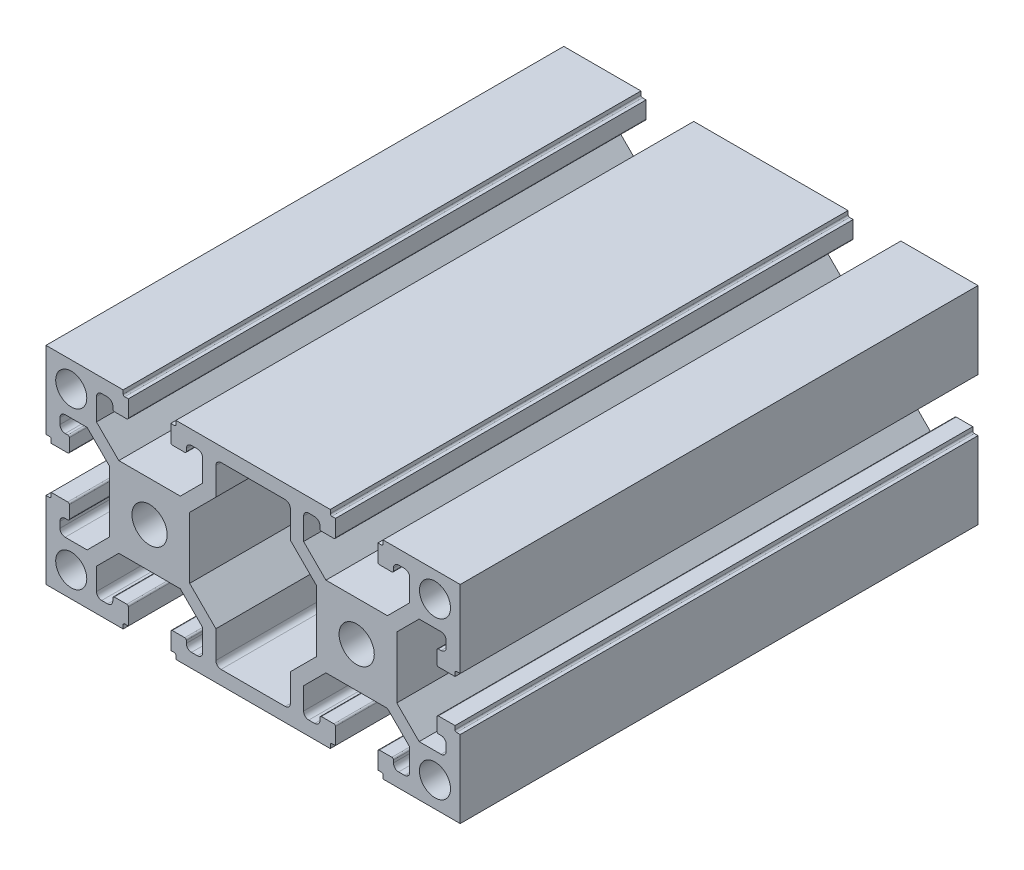
SolidWorks part; units mm, degrees
ref_plane "前视基准面" through (0, 0, 0) normal (0, 0, 1) x (1, 0, 0)
ref_plane "上视基准面" through (0, 0, 0) normal (0, 1, 0) x (1, 0, 0)
ref_plane "右视基准面" through (0, 0, 0) normal (1, 0, 0) x (0, 0, -1)
sketch "草图1" plane through (0, 0, 0) normal (0, 0, 1) x (1, 0, 0)
  line L0 (-26.1884, 19.243) -> (-41.0884, 19.243)
  line L1 (-41.0884, 19.243) -> (-41.0884, 4.343)
  line L2 (-33.1486, 9.493) -> (-37.3884, 9.493)
  line L3 (-38.3884, 8.493) -> (-38.3884, 7.343)
  line L4 (-37.3884, 6.343) -> (-36.8884, 6.343)
  line L5 (-36.5884, 6.043) -> (-36.5884, 3.643)
  line L6 (-36.8884, 3.343) -> (-40.0884, 3.343)
  line L8 (-41.0884, 4.343) -> (-40.3884, 4.343)
  line L9 (-40.0884, 4.043) -> (-40.0884, 3.343)
  line L10 (-28.8384, 5.1828) -> (-28.8384, -6.6968)
  line L11 (-27.0282, -8.507) -> (-15.1486, -8.507)
  line L12 (-15.1486, 6.993) -> (-27.0282, 6.993)
  line L13 (-26.1884, 19.243) -> (-26.1884, 18.543)
  line L14 (-25.8884, 18.243) -> (-25.1884, 18.243)
  line L15 (-31.3384, 11.3032) -> (-31.3384, 15.543)
  line L16 (-30.3384, 16.543) -> (-29.1884, 16.543)
  line L17 (-28.1884, 15.543) -> (-28.1884, 15.043)
  line L18 (-27.8884, 14.743) -> (-25.4884, 14.743)
  line L19 (-25.1884, 15.043) -> (-25.1884, 18.243)
  line L20 (-15.9884, 19.243) -> (-1.0884, 19.243)
  line L22 (-10.8384, 11.3032) -> (-10.8384, 15.543)
  line L23 (-8.2784, 10.2428) -> (-8.2784, 15.543)
  line L24 (-11.8384, 16.543) -> (-12.9884, 16.543)
  line L25 (-13.9884, 15.543) -> (-13.9884, 15.043)
  line L26 (-14.2884, 14.743) -> (-16.6884, 14.743)
  line L27 (-16.9884, 15.043) -> (-16.9884, 18.243)
  line L28 (-15.9884, 19.243) -> (-15.9884, 18.543)
  line L29 (-16.2884, 18.243) -> (-16.9884, 18.243)
  line L30 (-26.1884, -20.757) -> (-41.0884, -20.757)
  line L31 (-41.0884, -20.757) -> (-41.0884, -5.857)
  line L33 (-33.1486, -11.007) -> (-37.3884, -11.007)
  line L34 (-38.3884, -10.007) -> (-38.3884, -8.857)
  line L35 (-37.3884, -7.857) -> (-36.8884, -7.857)
  line L36 (-36.5884, -7.557) -> (-36.5884, -5.157)
  line L37 (-36.8884, -4.857) -> (-40.0884, -4.857)
  line L38 (-41.0884, -5.857) -> (-40.3884, -5.857)
  line L39 (-40.0884, -5.557) -> (-40.0884, -4.857)
  line L40 (-31.3384, -12.8172) -> (-31.3384, -17.057)
  line L41 (-30.3384, -18.057) -> (-29.1884, -18.057)
  line L42 (-28.1884, -17.057) -> (-28.1884, -16.557)
  line L43 (-27.8884, -16.257) -> (-25.4884, -16.257)
  line L44 (-25.1884, -16.557) -> (-25.1884, -19.757)
  line L45 (-26.1884, -20.757) -> (-26.1884, -20.057)
  line L46 (-25.8884, -19.757) -> (-25.1884, -19.757)
  line L47 (-15.9884, -20.757) -> (-1.0884, -20.757)
  line L49 (-10.8384, -12.8172) -> (-10.8384, -17.057)
  line L50 (-11.8384, -18.057) -> (-12.9884, -18.057)
  line L51 (-13.9884, -17.057) -> (-13.9884, -16.557)
  line L52 (-14.2884, -16.257) -> (-16.6884, -16.257)
  line L53 (-16.9884, -16.557) -> (-16.9884, -19.757)
  line L54 (-15.9884, -20.757) -> (-15.9884, -20.057)
  line L55 (-16.2884, -19.757) -> (-16.9884, -19.757)
  line L56 (-33.1486, 9.493) -> (-28.8384, 5.1828)
  line L57 (-31.3384, 11.3032) -> (-27.0282, 6.993)
  line L58 (-33.1486, -11.007) -> (-28.8384, -6.6968)
  line L59 (-31.3384, -12.8172) -> (-27.0282, -8.507)
  line L60 (-13.3384, 5.1828) -> (-13.3384, -6.6968)
  line L61 (-8.2784, 10.2428) -> (-13.3384, 5.1828)
  line L62 (-10.8384, 11.3032) -> (-15.1486, 6.993)
  line L63 (-8.2784, -11.7568) -> (-13.3384, -6.6968)
  line L64 (-10.8384, -12.8172) -> (-15.1486, -8.507)
  line L65 (24.0116, 19.243) -> (38.9116, 19.243)
  line L66 (38.9116, 19.243) -> (38.9116, 4.343)
  line L67 (30.9718, 9.493) -> (35.2116, 9.493)
  line L68 (36.2116, 8.493) -> (36.2116, 7.343)
  line L69 (35.2116, 6.343) -> (34.7116, 6.343)
  line L70 (34.4116, 6.043) -> (34.4116, 3.643)
  line L71 (34.7116, 3.343) -> (37.9116, 3.343)
  line L73 (38.9116, 4.343) -> (38.2116, 4.343)
  line L74 (37.9116, 4.043) -> (37.9116, 3.343)
  line L75 (26.6616, 5.1828) -> (26.6616, -6.6968)
  line L76 (24.8514, -8.507) -> (12.9718, -8.507)
  line L77 (12.9718, 6.993) -> (24.8514, 6.993)
  line L78 (24.0116, 19.243) -> (24.0116, 18.543)
  line L79 (23.7116, 18.243) -> (23.0116, 18.243)
  line L80 (29.1616, 11.3032) -> (29.1616, 15.543)
  line L81 (28.1616, 16.543) -> (27.0116, 16.543)
  line L82 (26.0116, 15.543) -> (26.0116, 15.043)
  line L83 (25.7116, 14.743) -> (23.3116, 14.743)
  line L84 (23.0116, 15.043) -> (23.0116, 18.243)
  line L85 (13.8116, 19.243) -> (-1.0884, 19.243)
  line L87 (8.6616, 11.3032) -> (8.6616, 15.543)
  line L88 (9.6616, 16.543) -> (10.8116, 16.543)
  line L89 (11.8116, 15.543) -> (11.8116, 15.043)
  line L90 (12.1116, 14.743) -> (14.5116, 14.743)
  line L91 (14.8116, 15.043) -> (14.8116, 18.243)
  line L92 (13.8116, 19.243) -> (13.8116, 18.543)
  line L93 (14.1116, 18.243) -> (14.8116, 18.243)
  line L94 (24.0116, -20.757) -> (38.9116, -20.757)
  line L95 (38.9116, -20.757) -> (38.9116, -5.857)
  line L97 (30.9718, -11.007) -> (35.2116, -11.007)
  line L98 (36.2116, -10.007) -> (36.2116, -8.857)
  line L99 (35.2116, -7.857) -> (34.7116, -7.857)
  line L100 (34.4116, -7.557) -> (34.4116, -5.157)
  line L101 (34.7116, -4.857) -> (37.9116, -4.857)
  line L102 (38.9116, -5.857) -> (38.2116, -5.857)
  line L103 (37.9116, -5.557) -> (37.9116, -4.857)
  line L104 (29.1616, -12.8172) -> (29.1616, -17.057)
  line L105 (28.1616, -18.057) -> (27.0116, -18.057)
  line L106 (26.0116, -17.057) -> (26.0116, -16.557)
  line L107 (25.7116, -16.257) -> (23.3116, -16.257)
  line L108 (23.0116, -16.557) -> (23.0116, -19.757)
  line L109 (24.0116, -20.757) -> (24.0116, -20.057)
  line L110 (23.7116, -19.757) -> (23.0116, -19.757)
  line L111 (13.8116, -20.757) -> (-1.0884, -20.757)
  line L113 (8.6616, -12.8172) -> (8.6616, -17.057)
  line L114 (9.6616, -18.057) -> (10.8116, -18.057)
  line L115 (11.8116, -17.057) -> (11.8116, -16.557)
  line L116 (12.1116, -16.257) -> (14.5116, -16.257)
  line L117 (14.8116, -16.557) -> (14.8116, -19.757)
  line L118 (13.8116, -20.757) -> (13.8116, -20.057)
  line L119 (14.1116, -19.757) -> (14.8116, -19.757)
  line L120 (30.9718, 9.493) -> (26.6616, 5.1828)
  line L121 (29.1616, 11.3032) -> (24.8514, 6.993)
  line L122 (30.9718, -11.007) -> (26.6616, -6.6968)
  line L123 (29.1616, -12.8172) -> (24.8514, -8.507)
  line L124 (11.1616, 5.1828) -> (11.1616, -6.6968)
  line L125 (6.1016, 10.2428) -> (11.1616, 5.1828)
  line L126 (8.6616, 11.3032) -> (12.9718, 6.993)
  line L127 (6.1016, -11.7568) -> (11.1616, -6.6968)
  line L128 (8.6616, -12.8172) -> (12.9718, -8.507)
  line L129 (-7.2784, 16.543) -> (5.1016, 16.543)
  line L131 (6.1016, 15.543) -> (6.1016, 10.2428)
  line L132 (-8.2784, -11.7568) -> (-8.2784, -17.057)
  line L133 (-7.2784, -18.057) -> (5.1016, -18.057)
  line L134 (6.1016, -17.057) -> (6.1016, -11.7568)
  arc A0 (-37.3884, 9.493) -> (-38.3884, 8.493) centre (-37.3884, 8.493) ccw
  arc A1 (-38.3884, 7.343) -> (-37.3884, 6.343) centre (-37.3884, 7.343) ccw
  arc A2 (-36.5884, 6.043) -> (-36.8884, 6.343) centre (-36.8884, 6.043) ccw
  arc A3 (-36.8884, 3.343) -> (-36.5884, 3.643) centre (-36.8884, 3.643) ccw
  arc A4 (-40.0884, 4.043) -> (-40.3884, 4.343) centre (-40.3884, 4.043) ccw
  circle A5 centre (-21.0884, -0.757) radius 3.4
  circle A6 centre (-36.2134, 14.368) radius 3
  arc A7 (-26.1884, 18.543) -> (-25.8884, 18.243) centre (-25.8884, 18.543) ccw
  arc A8 (-30.3384, 16.543) -> (-31.3384, 15.543) centre (-30.3384, 15.543) ccw
  arc A9 (-28.1884, 15.543) -> (-29.1884, 16.543) centre (-29.1884, 15.543) ccw
  arc A10 (-28.1884, 15.043) -> (-27.8884, 14.743) centre (-27.8884, 15.043) ccw
  arc A11 (-25.4884, 14.743) -> (-25.1884, 15.043) centre (-25.4884, 15.043) ccw
  arc A12 (-7.2784, 16.543) -> (-8.2784, 15.543) centre (-7.2784, 15.543) ccw
  arc A13 (-10.8384, 15.543) -> (-11.8384, 16.543) centre (-11.8384, 15.543) ccw
  arc A14 (-12.9884, 16.543) -> (-13.9884, 15.543) centre (-12.9884, 15.543) ccw
  arc A15 (-14.2884, 14.743) -> (-13.9884, 15.043) centre (-14.2884, 15.043) ccw
  arc A16 (-16.9884, 15.043) -> (-16.6884, 14.743) centre (-16.6884, 15.043) ccw
  arc A17 (-16.2884, 18.243) -> (-15.9884, 18.543) centre (-16.2884, 18.543) ccw
  arc A18 (-38.3884, -10.007) -> (-37.3884, -11.007) centre (-37.3884, -10.007) ccw
  arc A19 (-37.3884, -7.857) -> (-38.3884, -8.857) centre (-37.3884, -8.857) ccw
  arc A20 (-36.8884, -7.857) -> (-36.5884, -7.557) centre (-36.8884, -7.557) ccw
  arc A21 (-36.5884, -5.157) -> (-36.8884, -4.857) centre (-36.8884, -5.157) ccw
  arc A22 (-40.3884, -5.857) -> (-40.0884, -5.557) centre (-40.3884, -5.557) ccw
  circle A23 centre (-36.2134, -15.882) radius 3
  arc A24 (-31.3384, -17.057) -> (-30.3384, -18.057) centre (-30.3384, -17.057) ccw
  arc A25 (-29.1884, -18.057) -> (-28.1884, -17.057) centre (-29.1884, -17.057) ccw
  arc A26 (-27.8884, -16.257) -> (-28.1884, -16.557) centre (-27.8884, -16.557) ccw
  arc A27 (-25.1884, -16.557) -> (-25.4884, -16.257) centre (-25.4884, -16.557) ccw
  arc A28 (-25.8884, -19.757) -> (-26.1884, -20.057) centre (-25.8884, -20.057) ccw
  arc A29 (-11.8384, -18.057) -> (-10.8384, -17.057) centre (-11.8384, -17.057) ccw
  arc A30 (-13.9884, -17.057) -> (-12.9884, -18.057) centre (-12.9884, -17.057) ccw
  arc A31 (-13.9884, -16.557) -> (-14.2884, -16.257) centre (-14.2884, -16.557) ccw
  arc A32 (-16.6884, -16.257) -> (-16.9884, -16.557) centre (-16.6884, -16.557) ccw
  arc A33 (-15.9884, -20.057) -> (-16.2884, -19.757) centre (-16.2884, -20.057) ccw
  arc A34 (36.2116, 8.493) -> (35.2116, 9.493) centre (35.2116, 8.493) ccw
  arc A35 (35.2116, 6.343) -> (36.2116, 7.343) centre (35.2116, 7.343) ccw
  arc A36 (34.7116, 6.343) -> (34.4116, 6.043) centre (34.7116, 6.043) ccw
  arc A37 (34.4116, 3.643) -> (34.7116, 3.343) centre (34.7116, 3.643) ccw
  arc A38 (38.2116, 4.343) -> (37.9116, 4.043) centre (38.2116, 4.043) ccw
  circle A39 centre (18.9116, -0.757) radius 3.4
  circle A40 centre (34.0366, 14.368) radius 3
  arc A41 (23.7116, 18.243) -> (24.0116, 18.543) centre (23.7116, 18.543) ccw
  arc A42 (29.1616, 15.543) -> (28.1616, 16.543) centre (28.1616, 15.543) ccw
  arc A43 (27.0116, 16.543) -> (26.0116, 15.543) centre (27.0116, 15.543) ccw
  arc A44 (25.7116, 14.743) -> (26.0116, 15.043) centre (25.7116, 15.043) ccw
  arc A45 (23.0116, 15.043) -> (23.3116, 14.743) centre (23.3116, 15.043) ccw
  arc A46 (9.6616, 16.543) -> (8.6616, 15.543) centre (9.6616, 15.543) ccw
  arc A47 (11.8116, 15.543) -> (10.8116, 16.543) centre (10.8116, 15.543) ccw
  arc A48 (11.8116, 15.043) -> (12.1116, 14.743) centre (12.1116, 15.043) ccw
  arc A49 (14.5116, 14.743) -> (14.8116, 15.043) centre (14.5116, 15.043) ccw
  arc A50 (13.8116, 18.543) -> (14.1116, 18.243) centre (14.1116, 18.543) ccw
  arc A51 (35.2116, -11.007) -> (36.2116, -10.007) centre (35.2116, -10.007) ccw
  arc A52 (36.2116, -8.857) -> (35.2116, -7.857) centre (35.2116, -8.857) ccw
  arc A53 (34.4116, -7.557) -> (34.7116, -7.857) centre (34.7116, -7.557) ccw
  arc A54 (34.7116, -4.857) -> (34.4116, -5.157) centre (34.7116, -5.157) ccw
  arc A55 (37.9116, -5.557) -> (38.2116, -5.857) centre (38.2116, -5.557) ccw
  circle A56 centre (34.0366, -15.882) radius 3
  arc A57 (28.1616, -18.057) -> (29.1616, -17.057) centre (28.1616, -17.057) ccw
  arc A58 (26.0116, -17.057) -> (27.0116, -18.057) centre (27.0116, -17.057) ccw
  arc A59 (26.0116, -16.557) -> (25.7116, -16.257) centre (25.7116, -16.557) ccw
  arc A60 (23.3116, -16.257) -> (23.0116, -16.557) centre (23.3116, -16.557) ccw
  arc A61 (24.0116, -20.057) -> (23.7116, -19.757) centre (23.7116, -20.057) ccw
  arc A62 (8.6616, -17.057) -> (9.6616, -18.057) centre (9.6616, -17.057) ccw
  arc A63 (10.8116, -18.057) -> (11.8116, -17.057) centre (10.8116, -17.057) ccw
  arc A64 (12.1116, -16.257) -> (11.8116, -16.557) centre (12.1116, -16.557) ccw
  arc A65 (14.8116, -16.557) -> (14.5116, -16.257) centre (14.5116, -16.557) ccw
  arc A66 (14.1116, -19.757) -> (13.8116, -20.057) centre (14.1116, -20.057) ccw
  arc A67 (6.1016, 15.543) -> (5.1016, 16.543) centre (5.1016, 15.543) ccw
  arc A68 (-8.2784, -17.057) -> (-7.2784, -18.057) centre (-7.2784, -17.057) ccw
  arc A69 (5.1016, -18.057) -> (6.1016, -17.057) centre (5.1016, -17.057) ccw
extrude "凸台-拉伸1" add sketch "草图1" along normal blind 100
